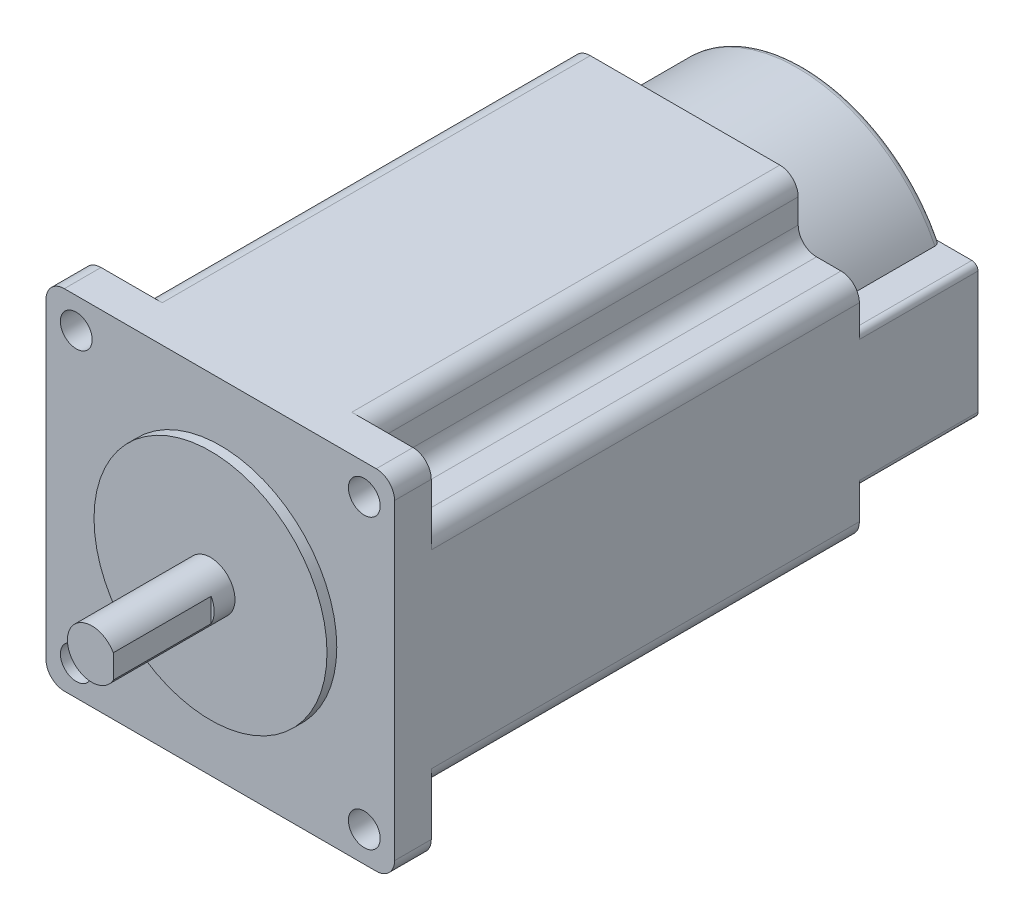
SolidWorks part; units mm, degrees
material "普通碳钢"
ref_plane "前视基准面" through (0, 0, 0) normal (0, 0, 1) x (1, 0, 0)
ref_plane "上视基准面" through (0, 0, 0) normal (0, 1, 0) x (1, 0, 0)
ref_plane "右视基准面" through (0, 0, 0) normal (1, 0, 0) x (0, 0, -1)
sketch "草图1" plane through (0, 0, 0) normal (0, 0, 1) x (1, 0, 0)
  line L1 (-38.6103, 28.1985) -> (18.3897, 28.1985)
  line L2 (-38.6103, 28.1985) -> (-38.6103, -28.8015)
  line L3 (-38.6103, -28.8015) -> (18.3897, -28.8015)
  line L4 (18.3897, 28.1985) -> (18.3897, -28.8015)
  dimension "D1" = 57
  dimension "D2" = 57
extrude "凸台-拉伸1" add sketch "草图1" along normal blind 76
sketch "草图2" plane through (0, 0, 0) normal (0, 0, -1) x (-1, 0, 0)
  line L1 (-18.3897, 28.1985) -> (-8.3897, 28.1985)
  line L2 (-18.3897, 28.1985) -> (-18.3897, 18.1985)
  line L3 (-18.3897, 18.1985) -> (-8.3897, 18.1985)
  line L4 (-8.3897, 28.1985) -> (-8.3897, 18.1985)
  line L5 (38.6103, 28.1985) -> (28.6103, 28.1985)
  line L6 (38.6103, 28.1985) -> (38.6103, 18.1985)
  line L7 (38.6103, 18.1985) -> (28.6103, 18.1985)
  line L8 (28.6103, 28.1985) -> (28.6103, 18.1985)
  line L9 (38.6103, -28.8015) -> (28.6103, -28.8015)
  line L10 (38.6103, -28.8015) -> (38.6103, -18.8015)
  line L11 (38.6103, -18.8015) -> (28.6103, -18.8015)
  line L12 (28.6103, -28.8015) -> (28.6103, -18.8015)
  line L13 (-18.3897, -28.8015) -> (-8.3897, -28.8015)
  line L14 (-18.3897, -28.8015) -> (-18.3897, -18.8015)
  line L15 (-18.3897, -18.8015) -> (-8.3897, -18.8015)
  line L16 (-8.3897, -28.8015) -> (-8.3897, -18.8015)
  dimension "D1" = 10
  dimension "D2" = 10
  dimension "D3" = 10
  dimension "D4" = 10
  dimension "D5" = 10
  dimension "D6" = 10
  dimension "D7" = 10
  dimension "D8" = 10
extrude "切除-拉伸1" cut sketch "草图2" against normal blind 70
sketch "草图3" plane through (0, 0, 76) normal (0, 0, 1) x (1, 0, 0)
  line L1 (18.3897, 28.1985) -> (-38.6103, 28.1985) construction
  line L3 (18.3897, -28.8015) -> (18.3897, 28.1985) construction
  line L4 (-38.6103, -28.8015) -> (18.3897, -28.8015) construction
  circle A0 centre (13.4397, 23.2485) radius 2.6
  circle A1 centre (-33.6603, 23.2485) radius 2.6
  circle A2 centre (-33.6603, -23.8515) radius 2.6
  circle A3 centre (13.4397, -23.8515) radius 2.6
  dimension "D1" = 5.2
  dimension "D2" = 5.2
  dimension "D3" = 5.2
  dimension "D4" = 5.2
  dimension "D5" = 47.1
  dimension "D6" = 4.95
  dimension "D7" = 4.95
  dimension "D8" = 47.1
  dimension "D9" = 47.1
  dimension "D10" = 47.1
  dimension "D11" = 4.95
  dimension "D12" = 4.95
extrude "切除-拉伸2" cut sketch "草图3" against normal through all
fillet "圆角2" radius 3 16 edges at (8.3897, -28.8015, 35) (8.3897, -18.8015, 35) (18.3897, -18.8015, 35) (18.3897, 18.1985, 35) (8.3897, 18.1985, 35) (8.3897, 28.1985, 35) (-28.6103, 28.1985, 35) (-28.6103, 18.1985, 35) (-38.6103, 18.1985, 35) (-28.6103, -18.8015, 35) (-28.6103, -28.8015, 35) (-38.6103, -18.8015, 35) (-38.6103, -28.8015, 73) (18.3897, -28.8015, 73) (18.3897, 28.1985, 73) (-38.6103, 28.1985, 73)
sketch "草图4" plane through (0, 0, 76) normal (0, 0, 1) x (1, 0, 0)
  circle A0 centre (-10.1103, -0.3015) radius 19.05
  dimension "D1" = 38.1
extrude "凸台-拉伸2" add sketch "草图4" along normal blind 1.6
sketch "草图5" plane through (0, 0, 77.6) normal (0, 0, 1) x (1, 0, 0)
  circle A0 centre (-10.1103, -0.3015) radius 4
  dimension "D1" = 8
extrude "凸台-拉伸3" add sketch "草图5" along normal blind 19.4
sketch "草图6" plane through (0, 0, 97) normal (0, 0, 1) x (1, 0, 0)
  line L0 (-6.6103, 1.635) -> (-6.6103, -2.238)
  arc A0 (-6.6103, -2.238) -> (-6.6103, 1.635) centre (-10.1103, -0.3015) ccw
extrude "切除-拉伸3" cut sketch "草图6" against normal blind 16
sketch "草图7" plane through (0, 0, 0) normal (0, 0, -1) x (-1, 0, 0)
  line L1 (-12.349, -10.9645) -> (-18.3897, -10.9645)
  line L2 (-18.3897, -15.8015) -> (-18.3897, 15.1985) construction
  line L3 (-18.3897, -10.9645) -> (-18.3897, 10.9974)
  line L4 (-18.3897, 10.9974) -> (-12.349, 10.9974)
  arc A0 (-12.349, 10.9974) -> (-12.349, -10.9645) centre (10.1102, 0.0165) cw
extrude "凸台-拉伸4" add sketch "草图7" along normal blind 19.4
fillet "圆角3" radius 1 1 edges at (18.3897, 10.9974, -9.7)
fillet "圆角4" radius 1 1 edges at (18.3897, -10.9645, -9.7)
fillet "圆角5" radius 1 1 edges at (-35.1102, 0.0165, -19.4)
